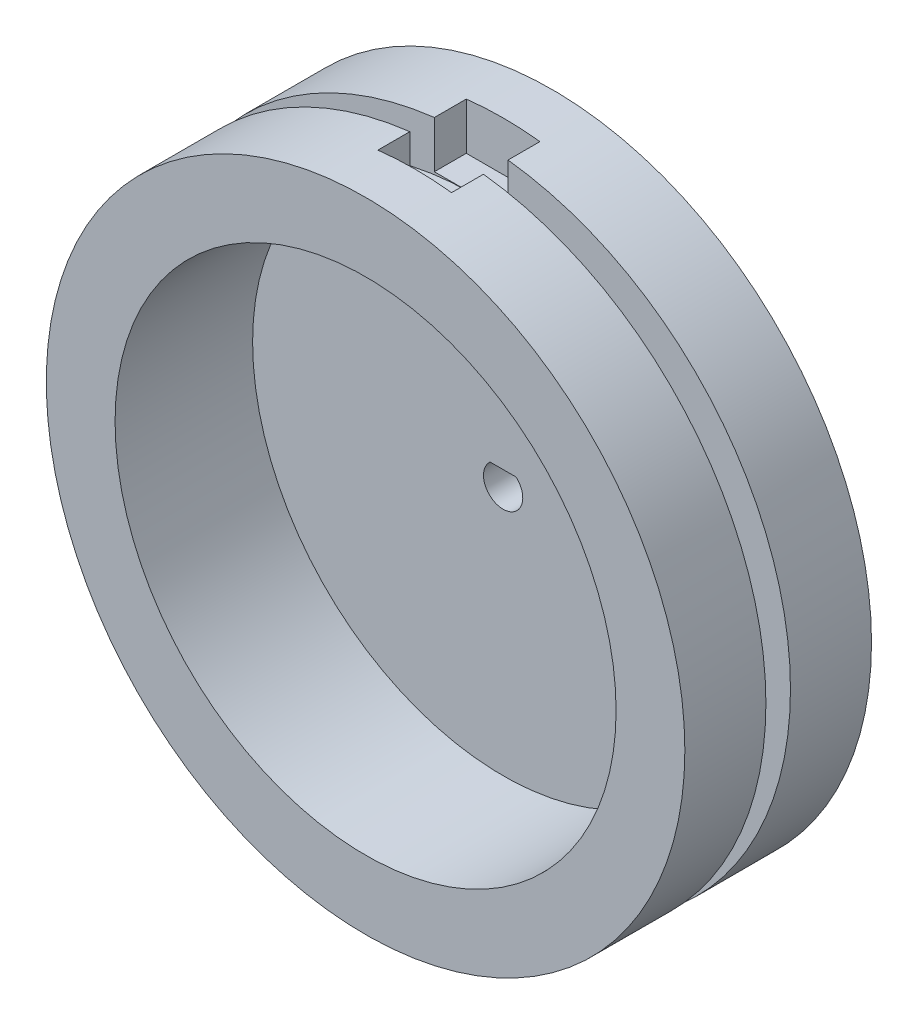
SolidWorks part; units mm, degrees
ref_plane "Front Plane" through (0, 0, 0) normal (0, 0, 1) x (1, 0, 0)
ref_plane "Top Plane" through (0, 0, 0) normal (0, 1, 0) x (1, 0, 0)
ref_plane "Right Plane" through (0, 0, 0) normal (1, 0, 0) x (0, 0, -1)
sketch "Sketch2" plane through (0, 0, 0) normal (1, 0, 0) x (0, 0, -1)
  line L0 (0, 0) -> (0, 32.5)
  line L1 (0, 32.5) -> (-8.25, 32.5)
  line L2 (-19, 32.5) -> (-19, 25.5)
  line L3 (-19, 25.5) -> (-5, 25.5)
  line L4 (-5, 25.5) -> (-5, 0)
  line L5 (-5, 0) -> (0, 0)
  line L6 (-8.25, 32.5) -> (-8.25, 27.5)
  line L7 (-8.25, 27.5) -> (-10.75, 27.5)
  line L8 (-10.75, 27.5) -> (-10.75, 32.5)
  line L9 (-10.75, 32.5) -> (-19, 32.5)
  dimension "D1" = 19
  dimension "D2" = 32.5
  dimension "D3" = 7
  dimension "D4" = 5
  dimension "D5" = 2.5
  dimension "D6" = 8.25
  dimension "D7" = 5
revolve "Revolve1" add sketch "Sketch2" angle 360 about L5
ref_plane "Plane1" through (0, 32.5, 0) normal (0, 1, 0) x (1, 0, 0)
sketch "Sketch7" plane through (0, 32.5, 0) normal (0, 1, 0) x (1, 0, 0)
  line L1 (-3.75, -14) -> (3.75, -14)
  line L2 (-3.75, -14) -> (-3.75, -5)
  line L3 (-3.75, -5) -> (3.75, -5)
  line L4 (3.75, -14) -> (3.75, -5)
  line L5 (-3.75, -9.5) -> (3.75, -9.5) construction
  line L6 (32.5, 0) -> (-32.5, 0) construction
  line L7 (0, -5) -> (0, 0) construction
  dimension "D1" = 9.5
  dimension "D2" = 9
  dimension "D3" = 7.5
extrude "Cut-Extrude1" cut sketch "Sketch7" against normal blind 5
mirror "Mirror1" about plane through (0, 0, 0) normal (0, 1, 0) of "Cut-Extrude1"
sketch "Sketch8" plane through (0, 0, 0) normal (0, 0, -1) x (-1, 0, 0)
  line L0 (-1.3229, 1.5) -> (1.3229, 1.5)
  arc A0 (-1.3229, 1.5) -> (1.3229, 1.5) centre (0, 0) ccw
  dimension "D1" = 4
  dimension "D2" = 1.5
extrude "Shaft Hole" cut sketch "Sketch8" against normal through all
